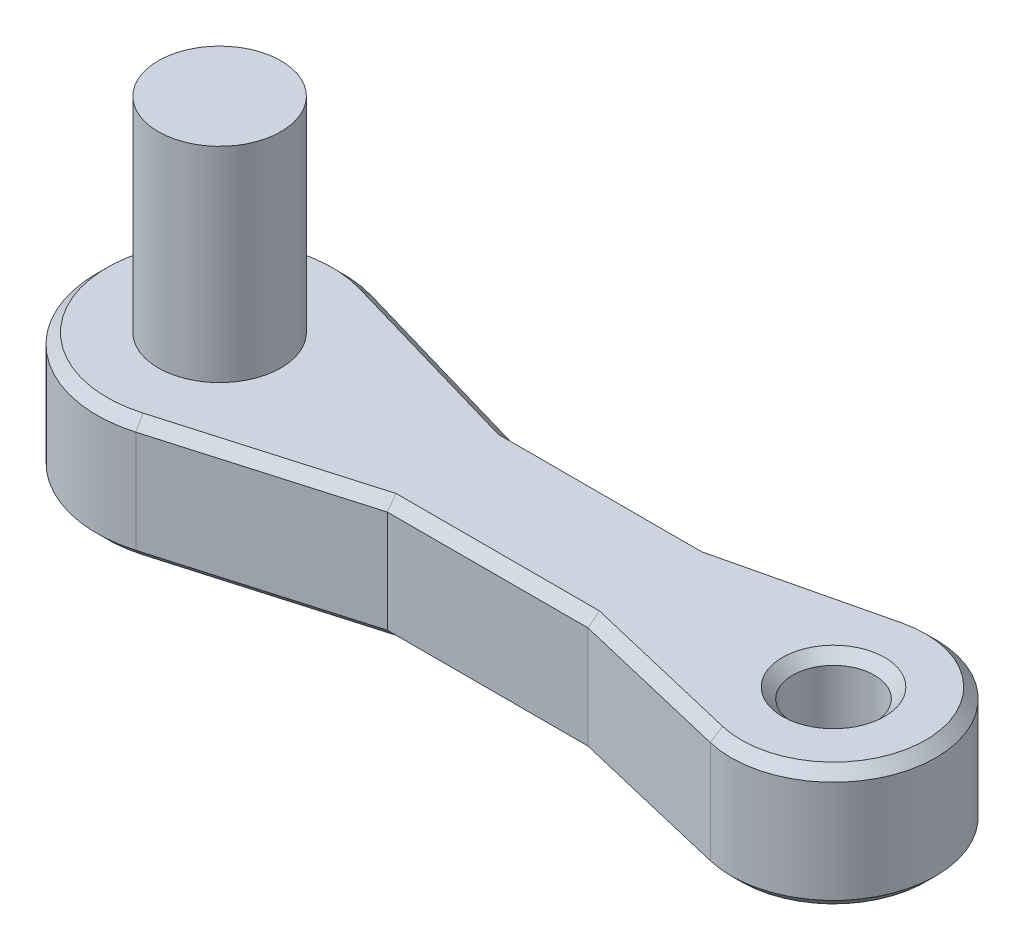
SolidWorks part; units mm, degrees
ref_plane "前视基准面" through (0, 0, 0) normal (0, 0, 1) x (1, 0, 0)
ref_plane "上视基准面" through (0, 0, 0) normal (0, 1, 0) x (1, 0, 0)
ref_plane "右视基准面" through (0, 0, 0) normal (1, 0, 0) x (0, 0, -1)
other "Configuration Table"
sketch "草图1" plane through (0, 0, 0) normal (0, 1, 0) x (1, 0, 0)
  circle A0 centre (0, 0) radius 1.5
  dimension "D1" = 3
extrude "凸台-拉伸1" add sketch "草图1" along normal blind 5
sketch "草图4" plane through (0, 0, 0) normal (0, 1, 0) x (1, 0, 0)
  line L0 (0, 0) -> (15, 0) construction
  line L1 (2.5981, 1.5) -> (13, 1.5)
  line L2 (2.5981, -1.5) -> (13, -1.5)
  arc A0 (2.5981, 1.5) -> (2.5981, -1.5) centre (0, 0) ccw
  arc A1 (13, -1.5) -> (13, 1.5) centre (15, 0) ccw
  dimension "D1" = 6
  dimension "D3" = 5
  dimension "D2" = 15
  dimension "D4" = 3
extrude "凸台-拉伸3" add sketch "草图4" against normal blind 3
sketch "草图5" plane through (0, 0, 0) normal (0, 1, 0) x (1, 0, 0)
  circle A0 centre (15, 0) radius 1
  dimension "D1" = 2
extrude "切除-拉伸2" cut sketch "草图5" against normal up to surface (3 mm away) up to face at (7.5245, -3, 0)
sketch "草图7" plane through (0, 0, 0) normal (0, 1, 0) x (1, 0, 0)
  line L0 (2.5981, -1.5) -> (13, -1.5) construction
  line L1 (13, 1.5) -> (2.5981, 1.5) construction
  line L2 (2.5981, -1.5) -> (13, -1.5) construction
  line L3 (13, 1.5) -> (2.5981, 1.5) construction
  line L4 (10.5, 1.5) -> (14.4219, 2.4322)
  line L5 (10.5, -1.5) -> (14.4219, -2.4322)
  line L6 (13, 1.5) -> (10.5, 1.5)
  line L7 (10.5, -1.5) -> (13, -1.5)
  arc A0 (13, -1.5) -> (13, 1.5) centre (15, 0) ccw construction
  arc A1 (13, -1.5) -> (14.4219, -2.4322) centre (15, 0) ccw
  arc A2 (14.4219, 2.4322) -> (13, 1.5) centre (15, 0) ccw
  dimension "D1" = 2.5
  dimension "D2" = 2.5
extrude "凸台-拉伸4" add sketch "草图7" against normal up to surface (3 mm away) up to face at (15, -3, 1)
sketch "草图9" plane through (0, 0, 0) normal (0, 1, 0) x (1, 0, 0)
  line L0 (10.5, 1.5) -> (2.5981, 1.5) construction
  line L1 (2.5981, -1.5) -> (10.5, -1.5) construction
  line L2 (5.5981, 1.5) -> (2.5981, 1.5)
  line L3 (2.5981, -1.5) -> (5.5981, -1.5)
  line L4 (5.5981, -1.5) -> (0.8357, -2.8813)
  line L5 (5.5981, 1.5) -> (0.8357, 2.8813)
  arc A0 (2.5981, 1.5) -> (2.5981, -1.5) centre (0, 0) ccw construction
  arc A1 (2.5981, 1.5) -> (0.8357, 2.8813) centre (0, 0) ccw
  arc A2 (0.8357, -2.8813) -> (2.5981, -1.5) centre (0, 0) ccw
  dimension "D1" = 3
  dimension "D2" = 3
extrude "凸台-拉伸5" add sketch "草图9" against normal up to surface (3 mm away) up to face at (8.7533, -3, 0)
chamfer "倒角2" distance 0.25 angle 45 18 edges at (-3, 0, 0) (3.2169, -3, -2.1906) (3.2169, 0, -2.1906) (3.2169, -3, 2.1906) (3.2169, 0, 2.1906) (8.049, 0, 1.5) (8.049, 0, -1.5) (12.4609, -3, -1.9661) (12.4609, 0, -1.9661) (12.4609, -3, 1.9661) (12.4609, 0, 1.9661) (17.5, 0, 0) (15, -3, 1) (-3, -3, 0) (8.049, -3, 1.5) (8.049, -3, -1.5) (17.5, -3, 0) (15, 0, 1)
